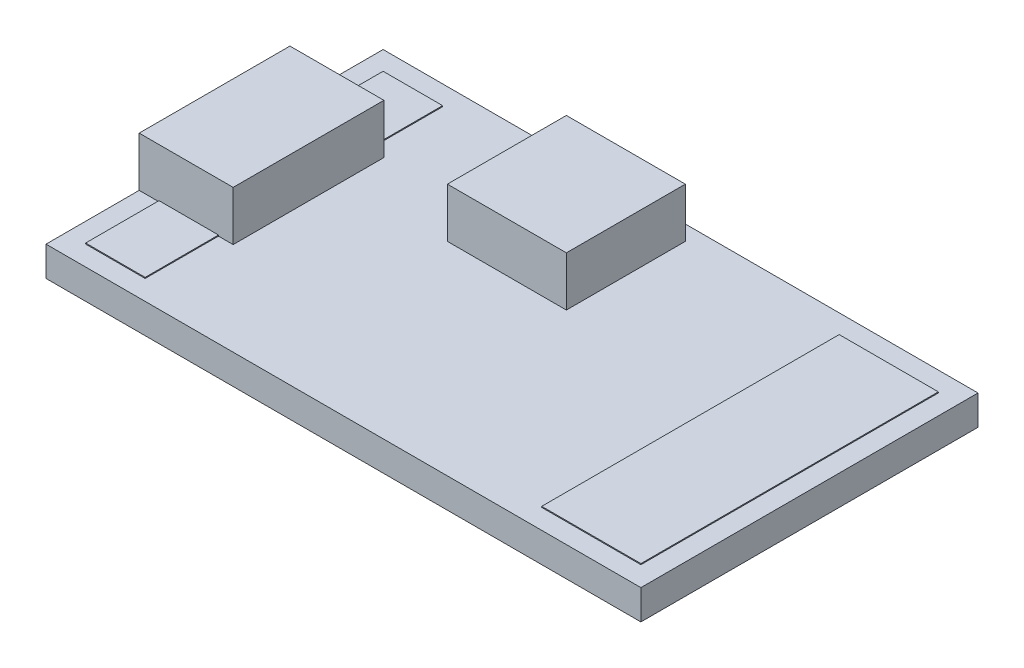
SolidWorks part; units mm, degrees
ref_plane "Спереди" through (0, 0, 0) normal (0, 0, 1) x (1, 0, 0)
ref_plane "Сверху" through (0, 0, 0) normal (0, 1, 0) x (1, 0, 0)
ref_plane "Справа" through (0, 0, 0) normal (1, 0, 0) x (0, 0, -1)
sketch "Эскиз1" plane through (0, 0, 0) normal (0, 1, 0) x (1, 0, 0)
  line L1 (0, 8.5) -> (-30, 8.5)
  line L2 (0, 8.5) -> (0, -8.5)
  line L3 (0, -8.5) -> (-30, -8.5)
  line L4 (-30, 8.5) -> (-30, -8.5)
  point P4 (0, 0)
  dimension "D1" = 17
  dimension "D2" = 30
extrude "Бобышка-Вытянуть1" add sketch "Эскиз1" along normal blind 1.5
sketch "Эскиз2" plane through (0, 0, 0) normal (0, 1, 0) x (1, 0, 0)
  line L1 (0, 7.5) -> (-10, 7.5)
  line L2 (0, 7.5) -> (0, -7.5)
  line L3 (0, -7.5) -> (-10, -7.5)
  line L4 (-10, 7.5) -> (-10, -7.5)
  point P4 (0, 0)
  dimension "D1" = 15
  dimension "D2" = 10
extrude "Бобышка-Вытянуть2" [suppressed] add sketch "Эскиз2" along normal blind 11
chamfer "Фаска1" [suppressed] distance 4 distance2 2
sketch "Эскиз3" [suppressed] plane through (0, 11, 0) normal (0, 1, 0) x (1, 0, 0)
  line L0 (-5, 5.5) -> (-5, -5.5) construction
  line L1 (0, 5.5) -> (-10, 5.5) construction
  line L2 (-10, -5.5) -> (0, -5.5) construction
sketch "Эскиз4" plane through (0, 0, 0) normal (0, 1, 0) x (1, 0, 0)
  line L0 (-30, 8.5) -> (-30, -8.5) construction
  line L1 (-20, 7.7414) -> (-14, 7.7414)
  line L2 (-20, 7.7414) -> (-20, 1.7414)
  line L3 (-20, 1.7414) -> (-14, 1.7414)
  line L4 (-14, 7.7414) -> (-14, 1.7414)
  line L9 (0, 0) -> (-30, 0) construction
  line L10 (-30, 8.5) -> (-30, -8.5) construction
  line L15 (0, 8.5) -> (0, -8.5) construction
  line L16 (-30, 3.8017) -> (-25.2605, 3.8017)
  line L17 (-30, 3.8017) -> (-30, -3.8017)
  line L18 (-30, -3.8017) -> (-25.2605, -3.8017)
  line L19 (-25.2605, 3.8017) -> (-25.2605, -3.8017)
  point P17 (-30, 3.5809)
  point P18 (-25.2605, 0)
  dimension "D1" = 20
  dimension "D2" = 6
extrude "Бобышка-Вытянуть3" add sketch "Эскиз4" along normal blind 4
sketch "Эскиз5" plane through (0, 0, 0) normal (0, 1, 0) x (1, 0, 0)
  line L0 (-30, 0) -> (0, 0)
  line L2 (-30, 3.8017) -> (-30, -3.8017) construction
  point P2 (-30, 0)
sketch "Эскиз6" plane through (0, 0, 0) normal (0, 1, 0) x (1, 0, 0)
  line L0 (-30, -8.5) -> (0, -8.5) construction
  line L1 (0, 8.5) -> (-7, 8.5) construction
  line L2 (0, 8.5) -> (0, -8.5) construction
  line L3 (0, -8.5) -> (-7, -8.5) construction
  line L4 (-7, 8.5) -> (-7, -8.5) construction
  line L5 (-1, 7.5) -> (-6, 7.5)
  line L6 (-30, 8.5) -> (-25, 8.5) construction
  line L7 (-30, 8.5) -> (-30, -8.5) construction
  line L8 (-30, -8.5) -> (-25, -8.5) construction
  line L9 (-25, 8.5) -> (-25, -8.5) construction
  line L10 (-6, 7.5) -> (-6, -7.5)
  line L11 (-1, -7.5) -> (-6, -7.5)
  line L12 (-1, 7.5) -> (-1, -7.5)
  line L13 (-29, 7.5) -> (-26, 7.5)
  line L14 (-26, 7.5) -> (-26, -7.5)
  line L15 (-29, -7.5) -> (-26, -7.5)
  line L16 (-29, 7.5) -> (-29, -7.5)
  dimension "D1" = 7
  dimension "D2" = 5
  dimension "D3" = 1
extrude "Бобышка-Вытянуть4" add sketch "Эскиз6" along normal offset from surface (1.55 mm away) 0.05 up to face at (-17, 1.5, -4.7414) offset beyond the face yes
